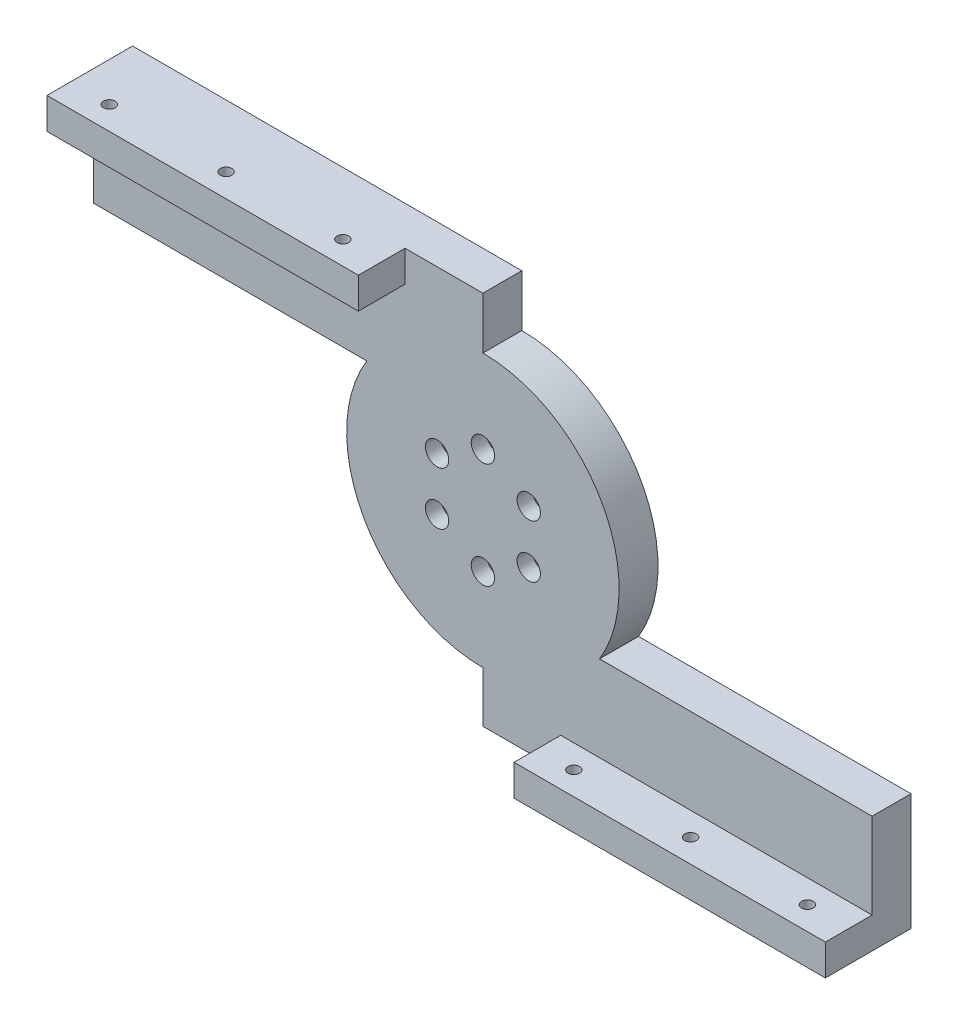
SolidWorks part; units mm, degrees
ref_plane "Front Plane" through (0, 0, 0) normal (0, 0, 1) x (1, 0, 0)
ref_plane "Top Plane" through (0, 0, 0) normal (0, 1, 0) x (1, 0, 0)
ref_plane "Right Plane" through (0, 0, 0) normal (1, 0, 0) x (0, 0, -1)
sketch "Sketch1" plane through (0, 0, 0) normal (0, 0, 1) x (1, 0, 0)
  line L1 (0, -48.0644) -> (100, -48.0644)
  line L2 (0, -48.0644) -> (0, -18.0644)
  line L3 (0, -18.0644) -> (100, -18.0644)
  line L4 (100, -48.0644) -> (100, -18.0644)
  line L5 (0, 48.3183) -> (-100, 48.3183)
  line L6 (0, 48.3183) -> (0, 18.3183)
  line L7 (0, 18.3183) -> (-100, 18.3183)
  line L8 (-100, 48.3183) -> (-100, 18.3183)
  circle A0 centre (0, 0) radius 35
  dimension "D1" = 70
  dimension "D2" = 30
  dimension "D3" = 30
  dimension "D4" = 100
  dimension "D5" = 100
extrude "Boss-Extrude2" add sketch "Sketch1" along normal blind 10 contours A0 L5 L8 L7 | L6 A0 L7 | L7 A0 L2 L3 L6 | L2 A0 L3 | A0 L1 L4 L3
sketch "Sketch2" plane through (0, 0, 10) normal (0, 0, 1) x (1, 0, 0)
  circle A0 centre (0, -13.5989) radius 3
  circle A1 centre (0, -13.5989) radius 1.5
  circle A2 centre (-11.777, -6.7994) radius 3
  circle A3 centre (-11.777, -6.7994) radius 1.5
  circle A4 centre (-11.777, 6.7994) radius 3
  circle A5 centre (-11.777, 6.7994) radius 1.5
  circle A6 centre (0, 13.5989) radius 3
  circle A7 centre (0, 13.5989) radius 1.5
  circle A8 centre (11.777, 6.7994) radius 3
  circle A9 centre (11.777, 6.7994) radius 1.5
  circle A10 centre (11.777, -6.7994) radius 3
  circle A11 centre (11.777, -6.7994) radius 1.5
  point P21 (0, 0)
  dimension "D1" = 6
  dimension "D2" = 3
  dimension "D3" = 6
extrude "Cut-Extrude2" cut sketch "Sketch2" against normal blind 4
sketch "Sketch3" plane through (0, 0, 10) normal (0, 0, 1) x (1, 0, 0)
  circle A0 centre (0, -13.5989) radius 1.5
  circle A1 centre (-11.777, -6.7994) radius 1.5
  circle A2 centre (-11.777, 6.7994) radius 1.5
  circle A3 centre (0, 13.5989) radius 1.5
  circle A4 centre (11.777, 6.7994) radius 1.5
  circle A5 centre (11.777, -6.7994) radius 1.5
  point P15 (0, 0)
  dimension "D1" = 6
extrude "Cut-Extrude3" cut sketch "Sketch3" against normal through all
sketch "Sketch5" plane through (0, 0, 10) normal (0, 0, 1) x (1, 0, 0)
  line L1 (-100, 48.3183) -> (-20, 48.3183)
  line L2 (-100, 48.3183) -> (-100, 40.3183)
  line L3 (-100, 40.3183) -> (-20, 40.3183)
  line L4 (-20, 48.3183) -> (-20, 40.3183)
  line L5 (100, -48.0644) -> (20, -48.0644)
  line L6 (100, -48.0644) -> (100, -40.0644)
  line L7 (100, -40.0644) -> (20, -40.0644)
  line L8 (20, -48.0644) -> (20, -40.0644)
  dimension "D1" = 8
  dimension "D2" = 80
  dimension "D3" = 8
  dimension "D4" = 80
extrude "Boss-Extrude3" add sketch "Sketch5" along normal blind 12
sketch "Sketch6" plane through (0, 40.3183, 0) normal (0, -1, 0) x (-1, 0, 0)
  circle A0 centre (89.9856, -16) radius 1.5
  circle A1 centre (59.9856, -16) radius 1.5
  circle A2 centre (29.9856, -16) radius 1.5
  dimension "D1" = 3
  dimension "D2" = 3
extrude "Cut-Extrude4" cut sketch "Sketch6" against normal through all
sketch "Sketch7" plane through (0, -40.0644, 0) normal (0, 1, 0) x (1, 0, 0)
  circle A0 centre (29.3725, -16) radius 1.5
  circle A1 centre (59.3725, -16) radius 1.5
  circle A2 centre (89.3725, -16) radius 1.5
  dimension "D1" = 3
  dimension "D2" = 3
extrude "Cut-Extrude5" cut sketch "Sketch7" against normal through all
